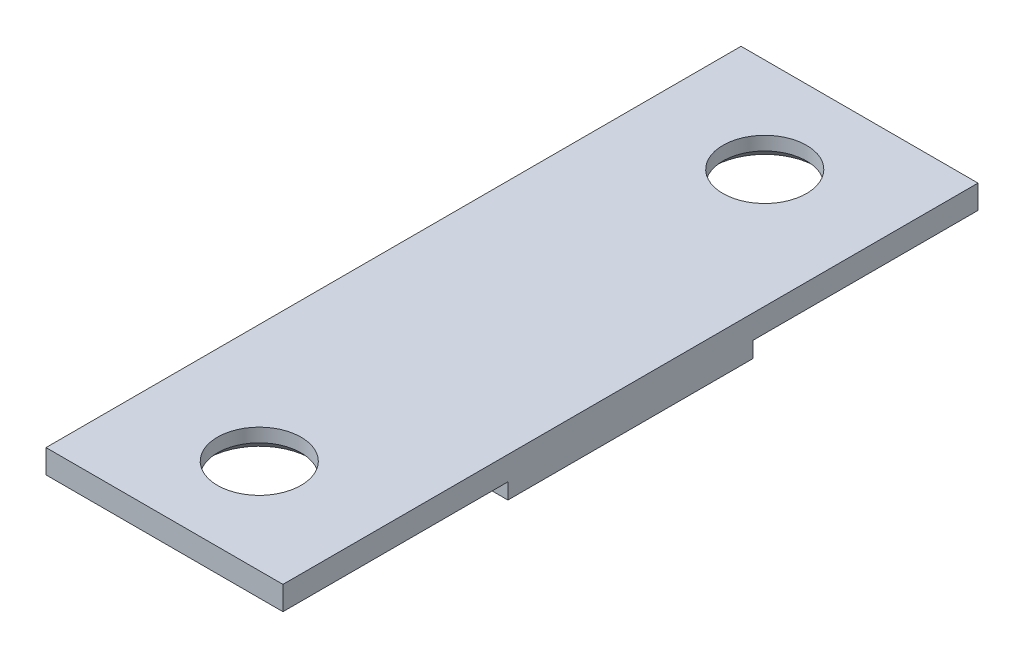
SolidWorks part; units mm, degrees
ref_plane "Front" through (0, 0, 0) normal (0, 0, 1) x (1, 0, 0)
ref_plane "Top" through (0, 0, 0) normal (0, 1, 0) x (1, 0, 0)
ref_plane "Right" through (0, 0, 0) normal (1, 0, 0) x (0, 0, -1)
sketch "Sketch1" plane through (0, 0, 0) normal (0, 1, 0) x (1, 0, 0)
  line L0 (0, 17.4625) -> (0, -17.4625) construction
  line L1 (-5.9531, 17.4625) -> (5.9531, 17.4625)
  line L2 (-5.9531, 17.4625) -> (-5.9531, -17.4625)
  line L3 (-5.9531, -17.4625) -> (5.9531, -17.4625)
  line L4 (5.9531, 17.4625) -> (5.9531, -17.4625)
  dimension "D1" = 11.9062
  dimension "D2" = 34.925
extrude "Extrude1" add sketch "Sketch1" along normal blind 1.9844
sketch "Sketch4" plane through (0, 0, 0) normal (0, -1, 0) x (1, 0, 0)
  line L0 (5.9531, 17.4625) -> (5.9531, -17.4625) construction
  line L1 (-5.9531, 17.4625) -> (5.9531, 17.4625)
  line L2 (-5.9531, 17.4625) -> (-5.9531, 6.1586)
  line L3 (-5.9531, 6.1586) -> (5.9531, 6.1586)
  line L4 (5.9531, 17.4625) -> (5.9531, 6.1586)
extrude "Extrude3" cut sketch "Sketch4" against normal offset from surface (0.7937 mm away) 1.1906 up to face at (0, 1.9844, 0)
mirror "Mirror1" about plane through (0, 0, 0) normal (0, 0, 1) of "Extrude3"
sketch "Sketch2" plane through (0, 1.9844, 0) normal (0, 1, 0) x (1, 0, 0)
  line L0 (0, 12.7) -> (0, -12.7) construction
  circle A0 centre (0, 12.7) radius 2.1
  circle A1 centre (0, -12.7) radius 2.1
  dimension "D2" = 4.2
  dimension "D1" = 25.4
extrude "Extrude2" cut sketch "Sketch2" against normal blind 1.9844
chamfer "Chamfer1" distance 0.508 angle 45 2 edges at (0, 0.7937, -10.6) (0, 0.7937, 14.8)
